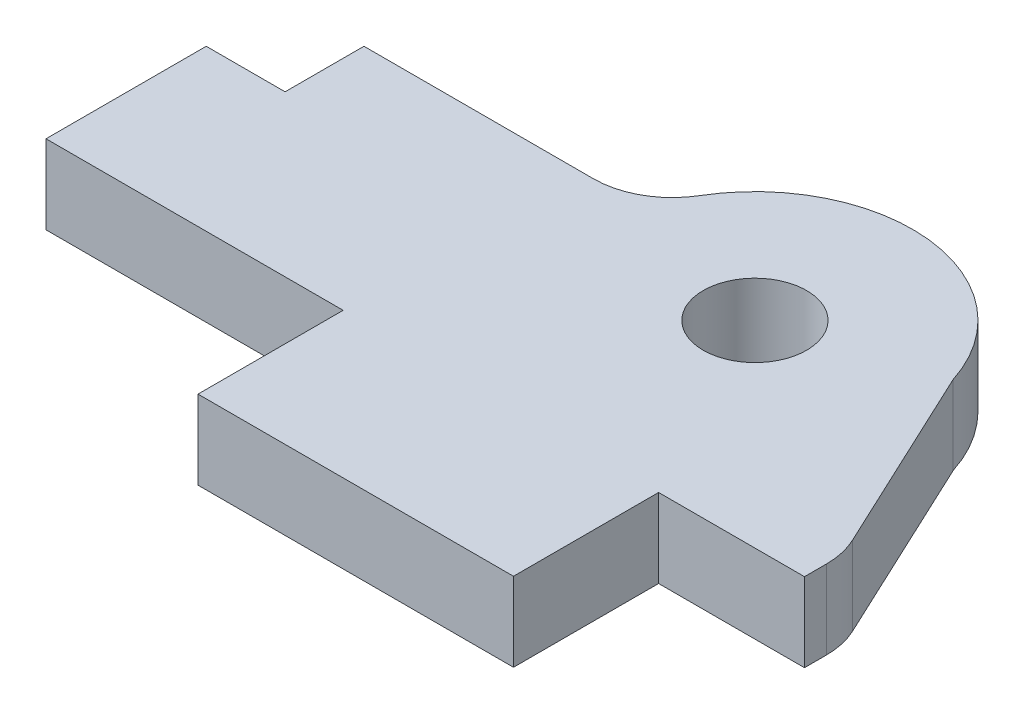
SolidWorks part; units mm, degrees
ref_plane "Front Plane" through (0, 0, 0) normal (0, 0, 1) x (1, 0, 0)
ref_plane "Top Plane" through (0, 0, 0) normal (0, 1, 0) x (1, 0, 0)
ref_plane "Right Plane" through (0, 0, 0) normal (1, 0, 0) x (0, 0, -1)
sketch "Sketch1" plane through (0, 0, 0) normal (0, 1, 0) x (1, 0, 0)
  line L0 (-15.9501, 2.921) -> (-18.3112, 2.921)
  line L1 (6.35, -2.921) -> (-6.35, -2.921)
  line L2 (6.35, -2.921) -> (6.35, 2.921)
  line L4 (-6.35, -2.921) -> (-6.35, 2.921)
  line L5 (6.35, -2.921) -> (-6.35, 2.921) construction
  line L6 (6.35, 2.921) -> (-6.35, -2.921) construction
  line L7 (-18.3112, 2.921) -> (-18.3112, 9.371)
  line L8 (-18.3112, 9.371) -> (-15.1362, 9.371)
  line L9 (-15.1362, 9.371) -> (-15.1362, 12.546)
  line L10 (-15.1362, 12.546) -> (-13.2044, 12.546)
  line L12 (12.2218, 4.5085) -> (12.2218, 2.921)
  line L13 (12.2218, 2.921) -> (6.35, 2.921)
  line L14 (-15.9501, 2.921) -> (-6.35, 2.921)
  line L15 (-13.2044, 12.546) -> (-3.8318, 12.546)
  line L16 (8.3389, 12.7902) -> (12.2218, 4.5085)
  circle A0 centre (2.2898, 10.8585) radius 2.0828
  arc A1 (8.3389, 12.7902) -> (-3.8318, 12.546) centre (2.2898, 10.8585) ccw
  point P0 (0, 0)
  dimension "D8" = 4.1656
  dimension "D9" = 12.7
  dimension "D1" = 5.842
  dimension "D2" = 12.7
  dimension "D3" = 6.45
  dimension "D4" = 1.5875
  dimension "D5" = 3.175
  dimension "D6" = 3.175
  dimension "D7" = 7.9375
  dimension "D10" = 17.426
extrude "Boss-Extrude1" add sketch "Sketch1" along normal blind 3.175
fillet "Fillet1" radius 3.175 2 edges at (12.2218, 1.5875, -4.5085) (-3.8318, 1.5875, -12.546)
